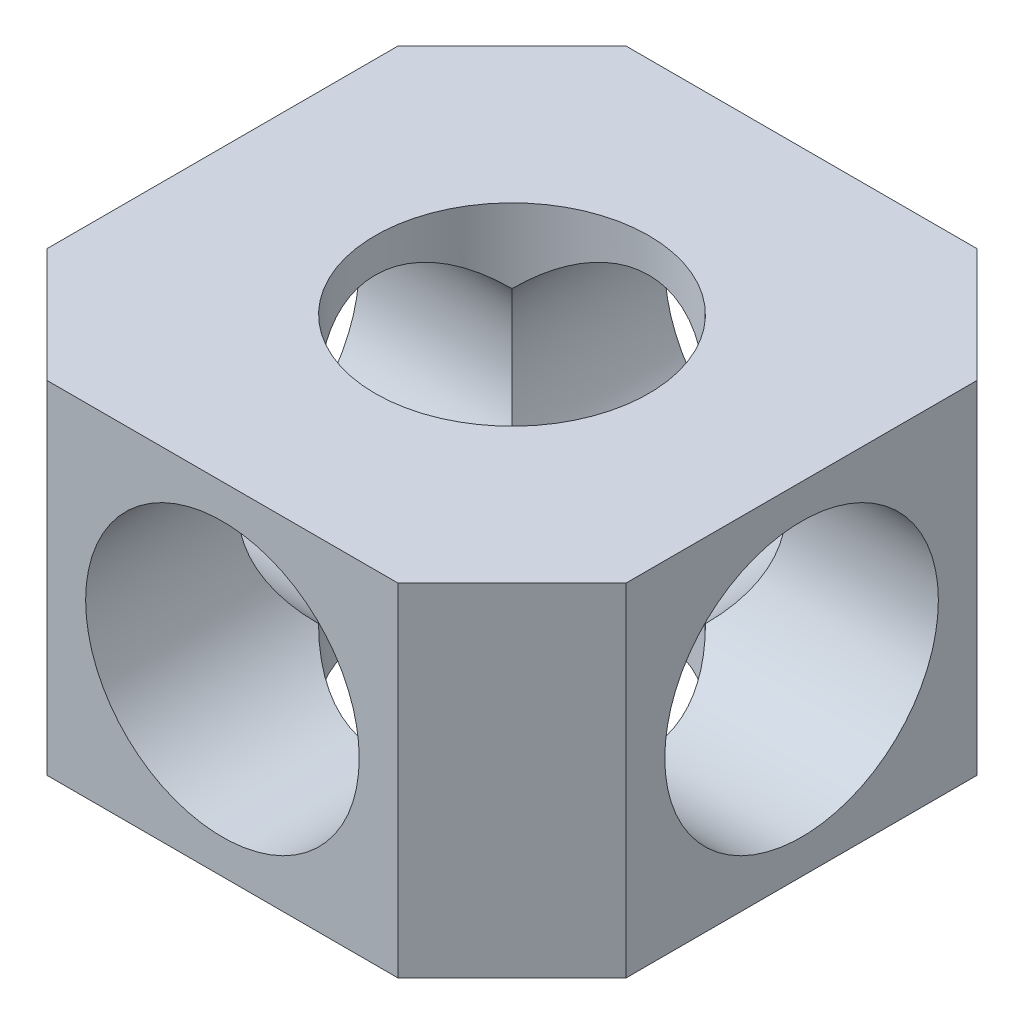
SolidWorks part; units mm, degrees
ref_plane "Front Plane" through (0, 0, 0) normal (0, 0, 1) x (1, 0, 0)
ref_plane "Top Plane" through (0, 0, 0) normal (0, 1, 0) x (1, 0, 0)
ref_plane "Right Plane" through (0, 0, 0) normal (1, 0, 0) x (0, 0, -1)
sketch "Sketch1" plane through (0, 0, 0) normal (0, 1, 0) x (1, 0, 0)
  line L1 (-12.7, 12.7) -> (12.7, 12.7)
  line L2 (-12.7, 12.7) -> (-12.7, -12.7)
  line L3 (-12.7, -12.7) -> (12.7, -12.7)
  line L4 (12.7, 12.7) -> (12.7, -12.7)
  line L5 (-12.7, 12.7) -> (12.7, -12.7) construction
  line L6 (-12.7, -12.7) -> (12.7, 12.7) construction
  point P0 (0, 0)
  dimension "D1" = 25.4
  dimension "D3" = 25.4
extrude "Boss-Extrude1" add sketch "Sketch1" along normal mid plane 15
chamfer "Chamfer1" distance 5 distance2 5 4 edges at (12.7, 0, -12.7) (-12.7, 0, -12.7) (-12.7, 0, 12.7) (12.7, 0, 12.7)
sketch "Sketch2" plane through (0, 7.5, 0) normal (0, 1, 0) x (1, 0, 0)
  circle A0 centre (0, 0) radius 6
  dimension "D1" = 12
extrude "Cut-Extrude1" cut sketch "Sketch2" against normal through all
sketch "Sketch3" plane through (0, 0, 12.7) normal (0, 0, 1) x (1, 0, 0)
  circle A0 centre (0, 0) radius 6
  dimension "D1" = 12
extrude "Cut-Extrude2" cut sketch "Sketch3" against normal through all
pattern_circular "CirPattern1" count 4 over 360 about axis through (0, -7.5, 0) along (0, 1, 0) of "Cut-Extrude2"
